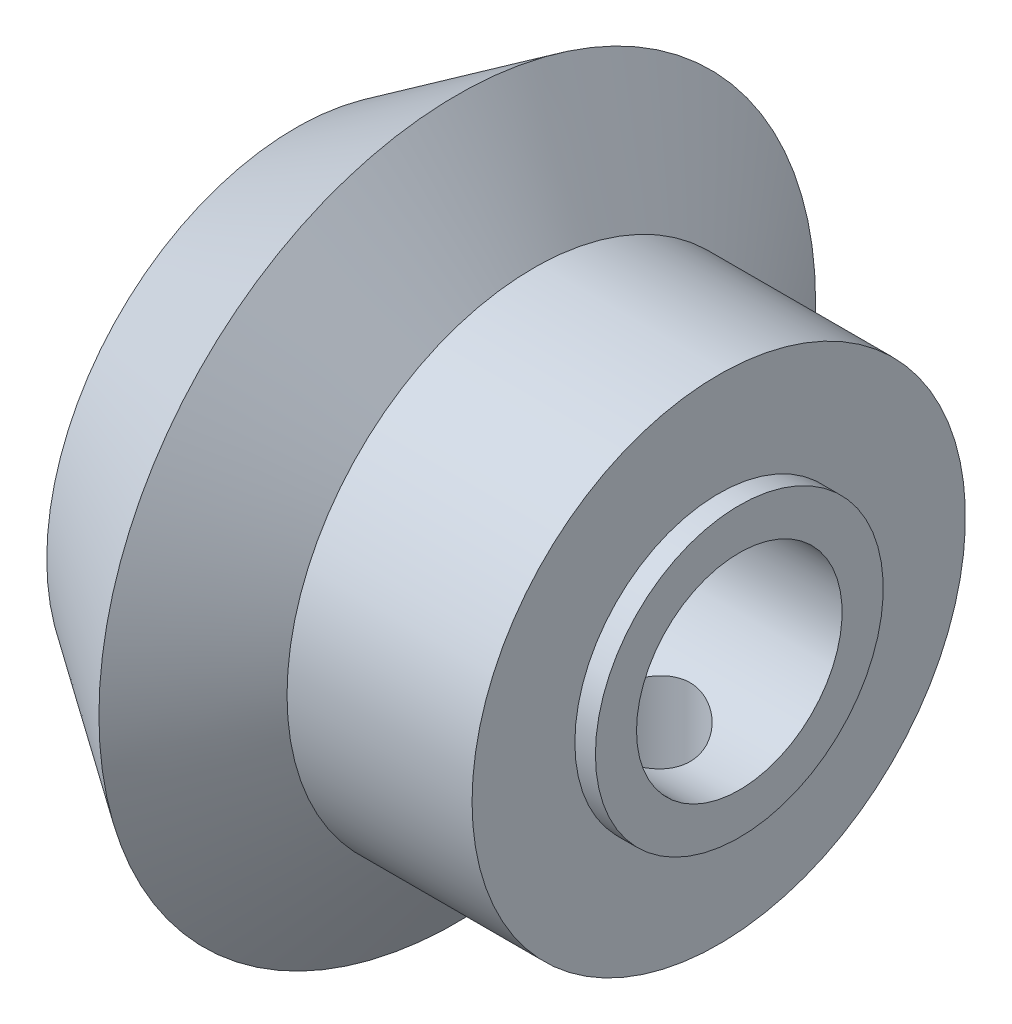
SolidWorks part; units mm, degrees
ref_plane "Front Plane" through (0, 0, 0) normal (0, 0, 1) x (1, 0, 0)
ref_plane "Top Plane" through (0, 0, 0) normal (0, 1, 0) x (1, 0, 0)
ref_plane "Right Plane" through (0, 0, 0) normal (1, 0, 0) x (0, 0, -1)
ref_plane "Plane1" through (0, 0, 0) normal (0, 0, -1) x (-1, 0, 0)
sketch "Sketch1" plane through (0, 0, 0) normal (0, 0, -1) x (-1, 0, 0)
  line L0 (-22.5, 3.5) -> (-22.5, 2.5)
  line L1 (-22.5, 2.5) -> (-12.5, 2.5)
  line L2 (-12.5, 2.5) -> (-12.5, 4.9)
  line L3 (-12.5, 4.9) -> (-11.71, 6.0531)
  line L4 (-11.71, 6.0531) -> (-15.64, 8.715)
  line L5 (-15.64, 8.715) -> (-17.5, 6)
  line L6 (-17.5, 6) -> (-22, 6)
  line L8 (-22.5, 0) -> (0, 0) construction
  line L11 (-22.5, 3.5) -> (-22, 3.5)
  line L12 (-22, 6) -> (-22, 3.5)
  point P0 (-22, 3.5)
  point P7 (0, 0)
  point P11 (0, 0)
  point P12 (0, 0)
  point P13 (0, 0)
  point P14 (0, 0)
  point P15 (0, 0)
  point P16 (0, 0)
  point P17 (0, 0)
  point P24 (-22, 3.5)
  dimension "D1" = 3.5
  dimension "D2" = 0.5
  dimension "D4" = 2.5
  dimension "D5" = 8.715
  dimension "D6" = 6
revolve "Revolve1" add sketch "Sketch1" angle 360 about L8
hole_wizard "Tap Drill for M3x0.5 Tap1" positions "3DSketch1" profile "Sketch2" hole size "M3x0.5" standard "JIS"
sketch3d "3DSketch1"
  point P0 (20, -6, 0)
  point P2 (0, 0, 0)
sketch "Sketch2" plane through (20, -6, 0) normal (1, 0, 0) x (0, 0, -1)
  line L0 (0, 0) -> (0, 3.5)
  line L1 (0, 3.5) -> (1.3, 3.5)
  line L2 (1.3, 3.5) -> (1.3, 0)
  line L5 (1.3, 0) -> (0, 0)
  line L11 (0, -6.35) -> (0, 107.95) construction
  dimension "Thru Hole Dia." = 2.6
  dimension "Thru Hole Depth" = 3.5
